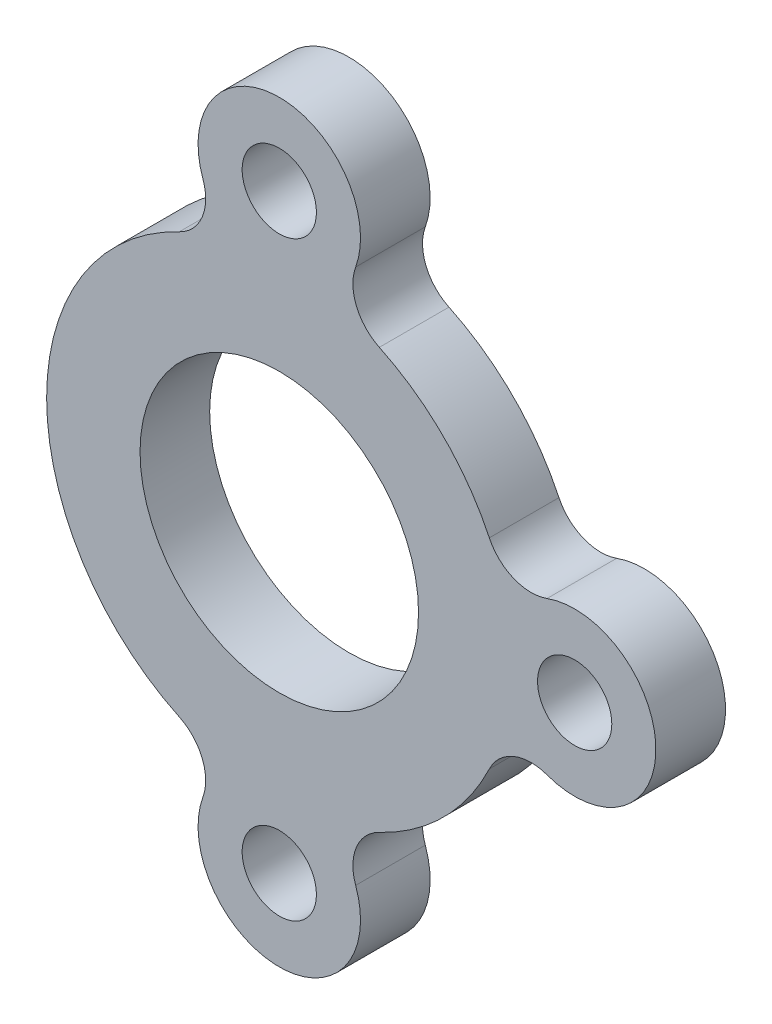
SolidWorks part; units mm, degrees
ref_plane "Front Plane" through (0, 0, 0) normal (0, 0, 1) x (1, 0, 0)
ref_plane "Top Plane" through (0, 0, 0) normal (0, 1, 0) x (1, 0, 0)
ref_plane "Right Plane" through (0, 0, 0) normal (1, 0, 0) x (0, 0, -1)
sketch "Sketch1" plane through (0, 0, 0) normal (0, 0, 1) x (1, 0, 0)
  circle A1 centre (16.8042, -17.2806) radius 1.6
  circle A5 centre (16.8042, -17.2806) radius 1.4 construction
  arc A6 (13.5131, -41.5453) -> (20.0953, -41.5453) centre (16.8042, -42.7365) ccw
  arc A7 (20.0953, -18.4718) -> (13.5131, -18.4718) centre (16.8042, -17.2806) ccw
  circle A9 centre (16.8042, -30.0086) radius 6
  arc A11 (28.341, -33.2996) -> (28.341, -26.7175) centre (29.5321, -30.0086) ccw
  circle A13 centre (16.8042, -30.0086) radius 8 construction
  arc A14 (13.8241, -40.901) -> (16.8042, -46.2365) centre (16.8042, -42.7365) ccw construction
  circle A15 centre (16.8042, -30.0086) radius 8 construction
  circle A16 centre (16.8042, -42.7365) radius 1.6
  circle A17 centre (29.5321, -30.0086) radius 1.6
  arc A20 (21.1157, -39.0591) -> (25.8547, -34.3201) centre (16.8042, -30.0086) ccw
  arc A21 (12.6927, -20.8655) -> (12.6927, -39.1517) centre (16.8042, -30.0086) ccw construction
  arc A22 (25.8547, -25.697) -> (21.1157, -20.9581) centre (16.8042, -30.0086) ccw
  arc A23 (12.4927, -20.9581) -> (12.4927, -39.0591) centre (16.8042, -30.0086) ccw
  arc A24 (20.0953, -41.5453) -> (21.1157, -39.0591) centre (21.9759, -40.8646) cw
  arc A25 (28.341, -33.2996) -> (25.8547, -34.3201) centre (27.6603, -35.1802) ccw
  arc A26 (28.341, -26.7175) -> (25.8547, -25.697) centre (27.6603, -24.8369) cw
  arc A27 (21.1157, -20.9581) -> (20.0953, -18.4718) centre (21.9759, -19.1525) cw
  arc A28 (12.4927, -20.9581) -> (13.5131, -18.4718) centre (11.6325, -19.1525) ccw
  arc A29 (13.5131, -41.5453) -> (12.4927, -39.0591) centre (11.6325, -40.8646) ccw
  dimension "D1" = 3.2
  dimension "D2" = 2
  dimension "D3" = 12
extrude "Boss-Extrude1" add sketch "Sketch1" along normal blind 3
